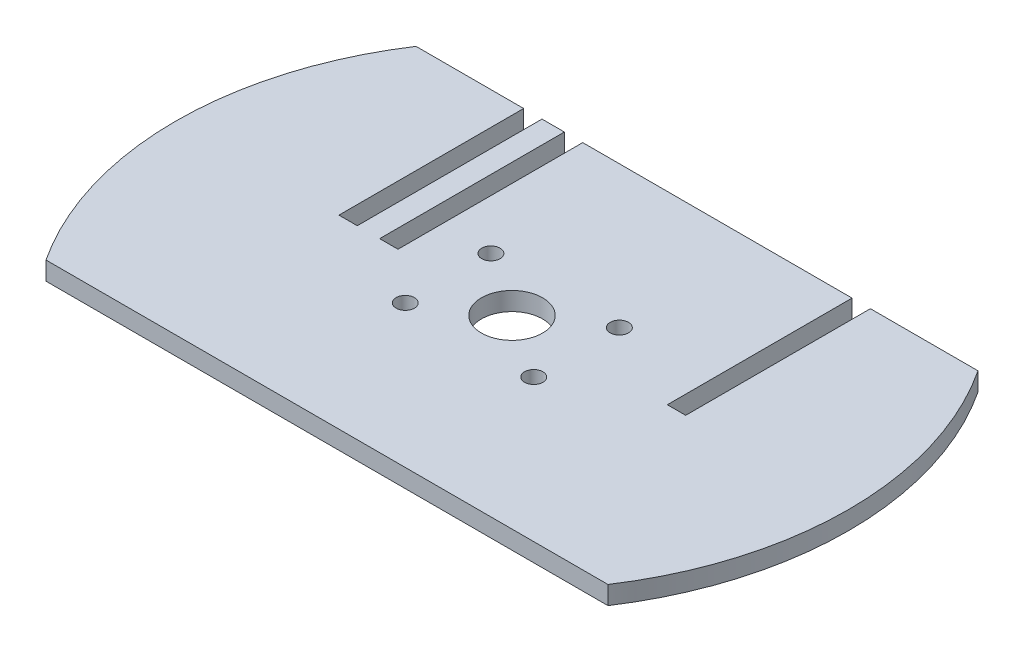
SolidWorks part; units mm, degrees
ref_plane "Front Plane" through (0, 0, 0) normal (0, 0, 1) x (1, 0, 0)
ref_plane "Top Plane" through (0, 0, 0) normal (0, 1, 0) x (1, 0, 0)
ref_plane "Right Plane" through (0, 0, 0) normal (1, 0, 0) x (0, 0, -1)
sketch "Sketch3" plane through (0, 0, 0) normal (0, 1, 0) x (1, 0, 0)
  line L0 (-42.1124, 3.703) -> (-22.1124, 3.703)
  line L1 (-22.1124, 3.703) -> (-22.1124, -26.497)
  line L2 (-22.1124, -26.497) -> (-19.1124, -26.497)
  line L3 (-19.1124, -26.497) -> (-19.1124, 3.703)
  line L4 (-19.1124, 3.703) -> (-15.4524, 3.703)
  line L8 (-12.4524, 3.703) -> (31.5776, 3.703)
  line L9 (31.5776, 3.703) -> (31.5776, -26.497)
  line L10 (31.5776, -26.497) -> (34.5776, -26.497)
  line L11 (34.5776, -26.497) -> (34.5776, 3.703)
  line L12 (34.5776, 3.703) -> (54.5776, 3.703)
  line L13 (64.5776, -6.297) -> (64.5776, -46.797)
  line L14 (54.5776, -56.797) -> (-42.1124, -56.797)
  line L15 (-52.1124, -6.297) -> (-52.1124, -46.797)
  line L16 (-15.4524, 3.703) -> (-12.4524, 3.703)
  arc A0 (54.5776, 3.703) -> (64.5776, -6.297) centre (54.5776, -6.297) cw
  arc A1 (-52.1124, -6.297) -> (-42.1124, 3.703) centre (-42.1124, -6.297) cw
  arc A2 (-42.1124, -56.797) -> (-52.1124, -46.797) centre (-42.1124, -46.797) cw
  arc A3 (54.5776, -56.797) -> (64.5776, -46.797) centre (54.5776, -46.797) ccw
  dimension "D8" = 10
  dimension "D1" = 60.5
  dimension "D2" = 3
  dimension "D4" = 3
  dimension "D5" = 30.2
  dimension "D6" = 44.03
  dimension "D7" = 3.66
  dimension "D9" = 30
  dimension "D10" = 30
extrude "Boss-Extrude1" add sketch "Sketch3" along normal blind 3 contours A3 L13 A0 L12 L11 L10 L9 L8 L16 L4 L3 L2 L1 L0 A1 L15 A2 L14
sketch "Sketch4" plane through (0, 3, 0) normal (0, 1, 0) x (1, 0, 0)
  line L0 (-52.1124, -6.297) -> (-52.1124, -46.797) construction
  line L2 (-19.1124, 3.703) -> (31.5776, 3.703) construction
  circle A0 centre (6.2326, -26.547) radius 5
  point P7 (-52.1124, -26.547)
  point P21 (6.2326, 3.703)
extrude "Cut-Extrude1" cut sketch "Sketch4" against normal blind 3 contours A0
sketch "Sketch6" plane through (0, 3, 0) normal (0, 1, 0) x (1, 0, 0)
  circle A0 centre (-4.2674, -19.497) radius 1.5
  circle A1 centre (-4.2674, -33.497) radius 1.5
  circle A2 centre (16.7326, -19.497) radius 1.5
  circle A3 centre (16.7326, -33.497) radius 1.5
  circle A4 centre (6.2326, -26.547) radius 5 construction
  dimension "D2" = 7
  dimension "D1" = 7
  dimension "D3" = 10.5
  dimension "D4" = 10.5
  dimension "D5" = 10.5
  dimension "D6" = 10.5
  dimension "D7" = 7
  dimension "D8" = 7
extrude "Cut-Extrude2" cut sketch "Sketch6" against normal blind 3
sketch "Sketch7" plane through (0, 3, 0) normal (0, 1, 0) x (1, 0, 0)
  line L0 (-42.1124, 3.703) -> (-22.1124, 3.703) construction
  line L1 (54.5776, -56.797) -> (-42.1124, -56.797) construction
  line L2 (34.5776, 3.703) -> (54.5776, 3.703) construction
  line L3 (52.1667, 3.703) -> (73.4592, 3.703)
  line L4 (73.4592, 3.703) -> (73.4592, -56.797)
  line L5 (73.4592, -56.797) -> (52.1667, -56.797)
  line L6 (-39.7014, 3.703) -> (-60.8199, 3.703)
  line L7 (-60.8199, 3.703) -> (-60.8199, -56.797)
  line L8 (-60.8199, -56.797) -> (-39.7014, -56.797)
  arc A0 (-39.7014, -56.797) -> (-39.7014, 3.703) centre (6.2326, -26.547) cw
  circle A1 centre (6.2326, -26.547) radius 5 construction
  arc A2 (52.1667, 3.703) -> (52.1667, -56.797) centre (6.2326, -26.547) cw
extrude "Cut-Extrude3" cut sketch "Sketch7" against normal blind 3
sketch "Sketch8" plane through (0, 3, 0) normal (0, 1, 0) x (1, 0, 0)
  line L0 (-15.4524, -26.497) -> (-15.4524, 3.703)
  line L1 (-19.1124, 3.703) -> (31.5776, 3.703) construction
  line L2 (-15.4524, 3.703) -> (-12.4524, 3.703)
  line L3 (-12.4524, 3.703) -> (-12.4524, -26.497)
  line L4 (-12.4524, -26.497) -> (-15.4524, -26.497)
  line L5 (-22.1124, -26.497) -> (-19.1124, -26.497) construction
  point P2 (0, 0)
  point P3 (0, 0)
  point P6 (0, 0)
  point P7 (0, 0)
  point P9 (0, 0)
  point P13 (0, 0)
  point P17 (-12.4524, 3.703)
  dimension "D1" = 3.66
  dimension "D2" = 3
extrude "Cut-Extrude4" cut sketch "Sketch8" against normal blind 3
